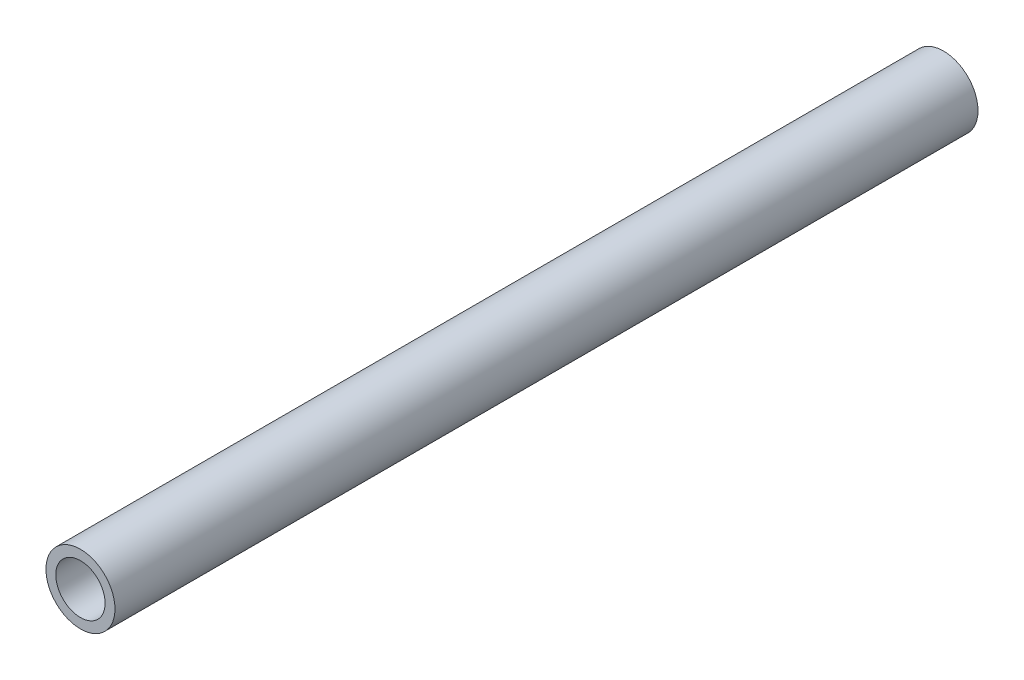
SolidWorks part; units mm, degrees
material "EM-CF"
ref_plane "Płaszczyzna przednia" through (0, 0, 0) normal (0, 0, 1) x (1, 0, 0)
ref_plane "Płaszczyzna górna" through (0, 0, 0) normal (0, 1, 0) x (1, 0, 0)
ref_plane "Płaszczyzna prawa" through (0, 0, 0) normal (1, 0, 0) x (0, 0, -1)
sketch "Szkic1" plane through (0, 0, 0) normal (0, 0, 1) x (1, 0, 0)
  circle A0 centre (0, 0) radius 5
  circle A1 centre (0, 0) radius 7
  dimension "D1" = 2
  dimension "D2" = 14
extrude "Dodanie-wyciągnięcie1" add sketch "Szkic1" along normal blind 175
